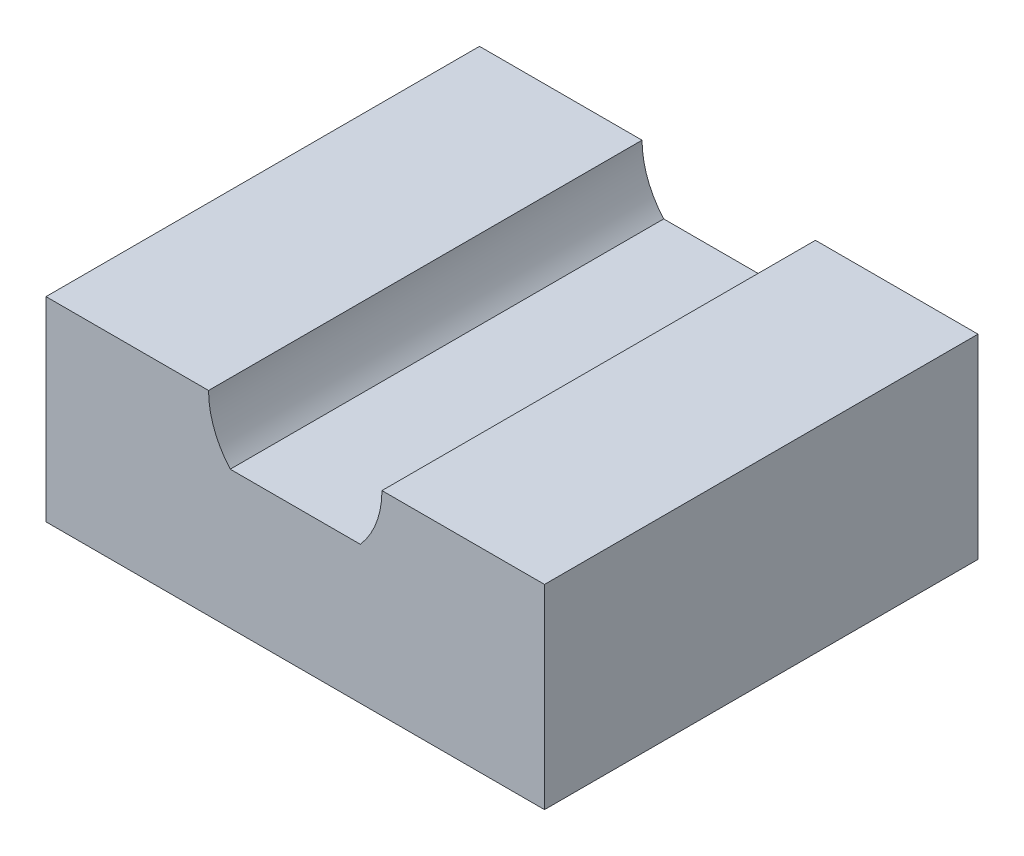
SolidWorks part; units mm, degrees
ref_plane "Piano frontale" through (0, 0, 0) normal (0, 0, 1) x (1, 0, 0)
ref_plane "Piano superiore" through (0, 0, 0) normal (0, 1, 0) x (1, 0, 0)
ref_plane "Piano destro" through (0, 0, 0) normal (1, 0, 0) x (0, 0, -1)
sketch "Schizzo1" plane through (0, 0, 0) normal (0, 0, 1) x (1, 0, 0)
  line L0 (-23, 18) -> (-23, 0)
  line L1 (-23, 0) -> (23, 0)
  line L2 (23, 0) -> (23, 18)
  line L3 (23, 18) -> (8, 18)
  line L4 (-23, 18) -> (-8, 18)
  line L5 (-6, 12.7085) -> (6, 12.7085)
  arc A0 (6, 12.7085) -> (8, 18) centre (0, 18) ccw
  arc A1 (-8, 18) -> (-6, 12.7085) centre (0, 18) ccw
  point P2 (0, 0)
  dimension "D2" = 16
  dimension "D1" = 12
  dimension "D3" = 15
  dimension "D4" = 18
extrude "Estrusione-Estrusione1" add sketch "Schizzo1" along normal blind 40
